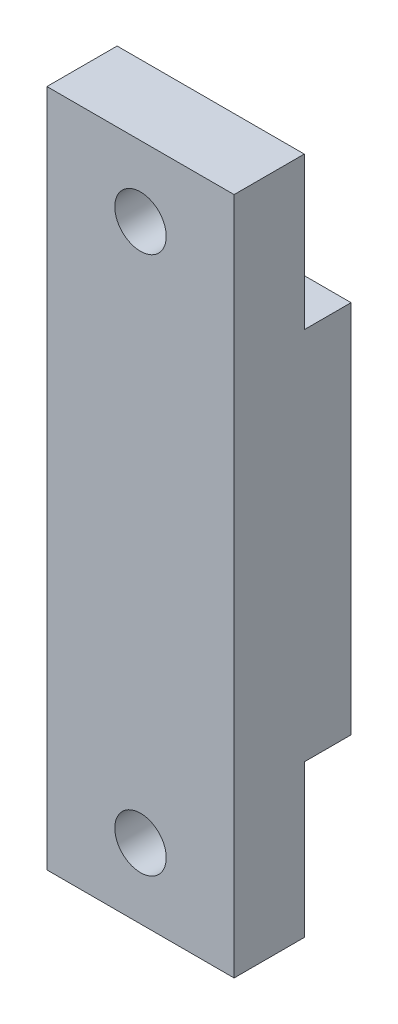
SolidWorks part; units mm, degrees
ref_plane "前视基准面" through (0, 0, 0) normal (0, 0, 1) x (1, 0, 0)
ref_plane "上视基准面" through (0, 0, 0) normal (0, 1, 0) x (1, 0, 0)
ref_plane "右视基准面" through (0, 0, 0) normal (1, 0, 0) x (0, 0, -1)
sketch "草图1" plane through (0, 0, 0) normal (0, 0, 1) x (1, 0, 0)
  line L1 (-4, 14.5) -> (4, 14.5)
  line L2 (-4, 14.5) -> (-4, -14.5)
  line L3 (-4, -14.5) -> (4, -14.5)
  line L4 (4, 14.5) -> (4, -14.5)
  line L5 (-4, 14.5) -> (4, -14.5) construction
  line L6 (-4, -14.5) -> (4, 14.5) construction
  point P0 (0, 0)
  dimension "D1" = 8
  dimension "D2" = 29
extrude "主体" add sketch "草图1" along normal blind 3
sketch "草图2" plane through (0, 0, 0) normal (0, 0, 1) x (1, 0, 0)
  line L0 (4, -14.5) -> (4, 14.5) construction
  line L1 (4, 8) -> (-4, 8)
  line L2 (4, 8) -> (4, -8)
  line L3 (4, -8) -> (-4, -8)
  line L4 (-4, 8) -> (-4, -8)
  line L5 (4, 8) -> (-4, -8) construction
  line L6 (4, -8) -> (-4, 8) construction
  point P0 (0, 0)
  dimension "D1" = 16
extrude "接线柱" add sketch "草图2" against normal blind 2
sketch "草图3" plane through (0, 0, 3) normal (0, 0, 1) x (1, 0, 0)
  line L0 (0, -3.905) -> (0, 3.905) construction
  line L1 (4, 14.5) -> (-4, 14.5) construction
  line L2 (3.905, 0) -> (-3.905, 0) construction
  circle A0 centre (0, 11.5) radius 1.1
  circle A1 centre (0, -11.5) radius 1.1
  point P2 (0, 0)
  dimension "D1" = 3
extrude "螺丝孔" cut sketch "草图3" against normal up to next
